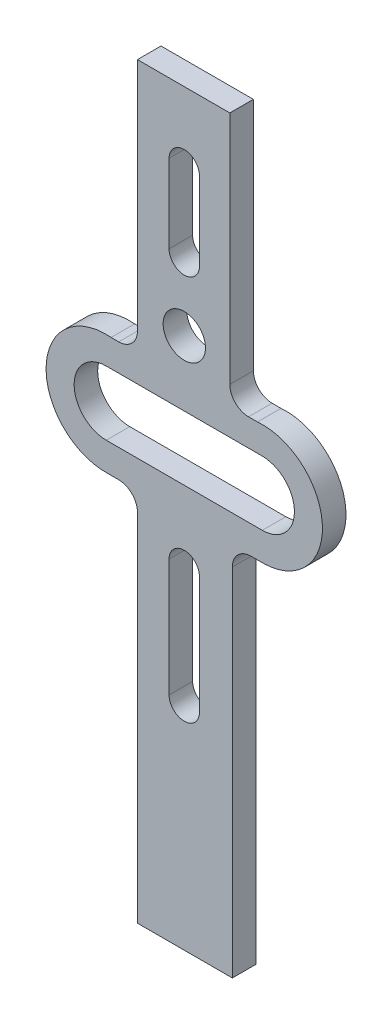
SolidWorks part; units mm, degrees
ref_plane "Front Plane" through (0, 0, 0) normal (0, 0, 1) x (1, 0, 0)
ref_plane "Top Plane" through (0, 0, 0) normal (0, 1, 0) x (1, 0, 0)
ref_plane "Right Plane" through (0, 0, 0) normal (1, 0, 0) x (0, 0, -1)
sketch "Sketch1" plane through (0, 0, 0) normal (0, 0, 1) x (1, 0, 0)
  line L0 (-4.011, 55.3091) -> (15.928, 55.3091) construction
  line L1 (0, 0) -> (12.08, 0)
  line L2 (0, 0) -> (0, 45.311)
  line L4 (12.08, 0) -> (12.08, 45.311)
  line L5 (-3.3584, 62.9011) -> (-2.381, 62.9011)
  line L6 (-3.7995, 47.692) -> (-2.381, 47.692)
  line L7 (14.141, 62.9011) -> (15.2754, 62.9011)
  line L8 (0, 95.2091) -> (11.76, 95.2091)
  line L9 (0, 95.2091) -> (0, 65.2821)
  line L11 (11.76, 95.2091) -> (11.76, 65.2821)
  line L12 (14.461, 47.692) -> (16.1395, 47.692)
  arc A0 (-3.3584, 62.9011) -> (-3.7995, 47.692) centre (-4.011, 55.3091) ccw
  arc A1 (16.1395, 47.692) -> (15.2754, 62.9011) centre (15.928, 55.3091) ccw
  arc A2 (-2.381, 62.9011) -> (0, 65.2821) centre (-2.381, 65.2821) ccw
  arc A3 (11.76, 65.2821) -> (14.141, 62.9011) centre (14.141, 65.2821) ccw
  arc A4 (0, 45.311) -> (-2.381, 47.692) centre (-2.381, 45.311) ccw
  arc A5 (14.461, 47.692) -> (12.08, 45.311) centre (14.461, 45.311) ccw
  point P7 (5.5705, 55.35)
  dimension "D4" = 7.62
  dimension "D5" = 4.011
  dimension "D8" = 4.762
  dimension "D9" = 4.762
  dimension "D10" = 4.762
  dimension "D11" = 4.762
  dimension "D12" = 7.62
  dimension "D13" = 29.927
  dimension "D2" = 19.939
  dimension "D3" = 12.08
  dimension "D6" = 11.76
  dimension "D7" = 4.011
  dimension "D14" = 29.927
  dimension "D15" = 45.311
  dimension "D16" = 45.311
extrude "Boss-Extrude1" add sketch "Sketch1" along normal blind 2.997
sketch "Sketch2" plane through (0, 0, 2.997) normal (0, 0, 1) x (1, 0, 0)
  line L0 (0, 95.2091) -> (0, 65.2821) construction
  line L1 (11.76, 95.2091) -> (0, 95.2091) construction
  circle A0 centre (5.959, 67.7261) radius 2.6925
  dimension "D1" = 5.385
  dimension "D2" = 5.959
  dimension "D3" = 27.483
extrude "Cut-Extrude1" cut sketch "Sketch2" against normal through all
sketch "Sketch3" plane through (0, 0, 2.997) normal (0, 0, 1) x (1, 0, 0)
  line L0 (-3.9709, 55.3515) -> (15.8901, 55.3515) construction
  line L1 (-3.9709, 59.441) -> (15.8901, 59.441)
  line L2 (-3.9709, 51.262) -> (15.8901, 51.262)
  line L3 (0, 0) -> (12.08, 0) construction
  arc A0 (-3.9709, 59.441) -> (-3.9709, 51.262) centre (-3.9709, 55.3515) ccw
  arc A1 (15.8901, 51.262) -> (15.8901, 59.441) centre (15.8901, 55.3515) ccw
  arc A4 (-3.3584, 62.9011) -> (-3.7995, 47.692) centre (-4.011, 55.3091) ccw construction
  point P2 (5.9596, 55.3515)
  point P12 (-11.6278, 55.53)
  dimension "D1" = 4.0895
  dimension "D2" = 51.262
  dimension "D3" = 19.861
  dimension "D4" = 7.659
extrude "Cut-Extrude2" cut sketch "Sketch3" against normal through all
sketch "Sketch4" plane through (0, 0, 2.997) normal (0, 0, 1) x (1, 0, 0)
  line L0 (5.9585, 86.3441) -> (5.9585, 76.3621) construction
  line L1 (7.889, 86.3441) -> (7.889, 76.3621)
  line L2 (4.028, 86.3441) -> (4.028, 76.3621)
  line L3 (0, 95.2091) -> (0, 65.2821) construction
  line L4 (11.76, 95.2091) -> (0, 95.2091) construction
  arc A0 (7.889, 86.3441) -> (4.028, 86.3441) centre (5.9585, 86.3441) ccw
  arc A1 (4.028, 76.3621) -> (7.889, 76.3621) centre (5.9585, 76.3621) ccw
  point P2 (5.9585, 81.3531)
  point P9 (0, 80.2456)
  point P10 (5.9585, 88.2746)
  point P13 (5.88, 95.2091)
  dimension "D2" = 1.9305
  dimension "D1" = 9.982
  dimension "D3" = 4.028
  dimension "D4" = 6.9345
extrude "Cut-Extrude3" cut sketch "Sketch4" against normal through all contours L1 A1 L2 A0
sketch "Sketch5" plane through (0, 0, 2.997) normal (0, 0, 1) x (1, 0, 0)
  line L0 (5.9585, 42.164) -> (5.9585, 27.178) construction
  line L1 (7.889, 42.164) -> (7.889, 27.178)
  line L2 (4.028, 42.164) -> (4.028, 27.178)
  line L3 (0, 0) -> (12.08, 0) construction
  line L4 (0, 45.311) -> (0, 0) construction
  arc A0 (7.889, 42.164) -> (4.028, 42.164) centre (5.9585, 42.164) ccw
  arc A1 (4.028, 27.178) -> (7.889, 27.178) centre (5.9585, 27.178) ccw
  point P2 (5.9585, 34.671)
  point P9 (6.04, 0)
  dimension "D2" = 1.9305
  dimension "D3" = 27.178
  dimension "D1" = 14.986
  dimension "D4" = 4.028
extrude "Cut-Extrude4" cut sketch "Sketch5" against normal through all
